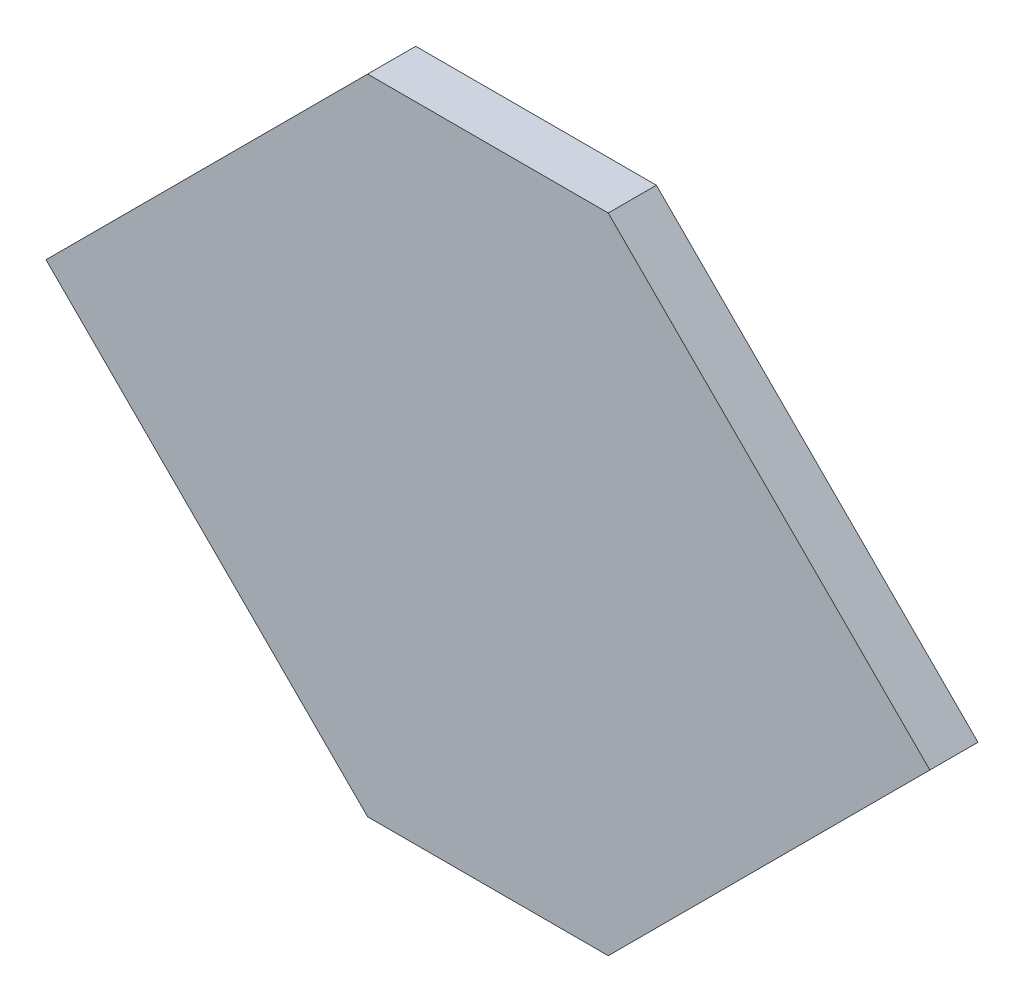
SolidWorks part; units mm, degrees
ref_plane "Plan de face" through (0, 0, 0) normal (0, 0, 1) x (1, 0, 0)
ref_plane "Plan de dessus" through (0, 0, 0) normal (0, 1, 0) x (1, 0, 0)
ref_plane "Plan de droite" through (0, 0, 0) normal (1, 0, 0) x (0, 0, -1)
sketch "Esquisse2" plane through (0, 0, 0) normal (0, 0, 1) x (1, 0, 0)
  line L0 (-49.6719, 0) -> (75.672, 0) construction
  line L1 (0, 58.4033) -> (0, -66.1645) construction
  line L2 (-25, 66.82) -> (25, 66.82)
  line L3 (25, 66.82) -> (91.82, 0)
  line L4 (25, 66.82) -> (25, 0) construction
  line L5 (-25, -66.82) -> (25, -66.82)
  line L6 (25, -66.82) -> (91.82, 0)
  line L7 (-25, -66.82) -> (-91.82, 0)
  line L8 (-25, 66.82) -> (-91.82, 0)
  point P12 (0, 66.82)
  point P13 (0, -66.82)
  dimension "D1" = 25
  dimension "D2" = 45
  dimension "D3" = 66.82
extrude "Boss.-Extru.2" add sketch "Esquisse2" along normal blind 10 contours L6 L3 L2 L8 L7 L5
